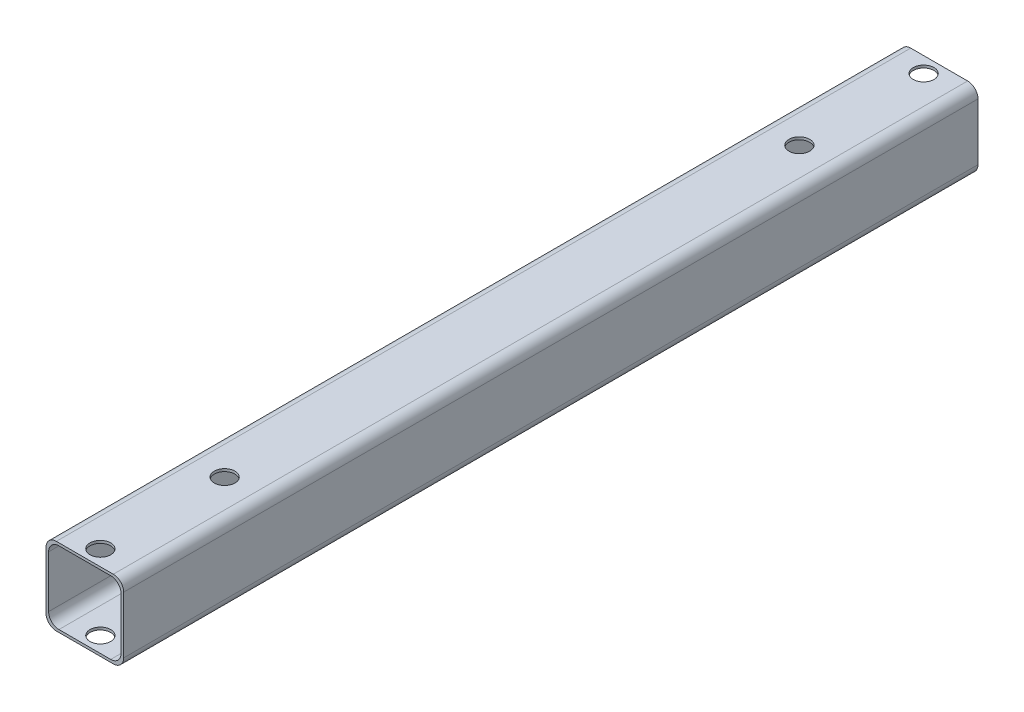
SolidWorks part; units mm, degrees
ref_plane "Front Plane" through (0, 0, 0) normal (0, 0, 1) x (1, 0, 0)
ref_plane "Top Plane" through (0, 0, 0) normal (0, 1, 0) x (1, 0, 0)
ref_plane "Right Plane" through (0, 0, 0) normal (1, 0, 0) x (0, 0, -1)
sketch "Sketch1" plane through (0, 0, 0) normal (0, 0, 1) x (1, 0, 0)
  line L1 (7.5, -7.5) -> (-7.5, -7.5)
  line L2 (7.5, -7.5) -> (7.5, 7.5)
  line L3 (7.5, 7.5) -> (-7.5, 7.5)
  line L4 (-7.5, -7.5) -> (-7.5, 7.5)
  line L5 (7.5, -7.5) -> (-7.5, 7.5) construction
  line L6 (7.5, 7.5) -> (-7.5, -7.5) construction
  line L7 (7, -7) -> (-7, -7)
  line L8 (7, -7) -> (7, 7)
  line L9 (7, 7) -> (-7, 7)
  line L10 (-7, -7) -> (-7, 7)
  line L11 (7, -7) -> (-7, 7) construction
  line L12 (7, 7) -> (-7, -7) construction
  point P0 (0, 0)
  point P6 (0, 0)
extrude "Boss-Extrude1" add sketch "Sketch1" along normal blind 165
fillet "Fillet1" radius 2 8 edges at (7, -7, 82.5) (7, 7, 82.5) (-7, -7, 82.5) (-7, 7, 82.5) (-7.5, -7.5, 82.5) (7.5, -7.5, 82.5) (7.5, 7.5, 82.5) (-7.5, 7.5, 82.5)
sketch "Sketch2" plane through (0, -7.5, 0) normal (0, -1, 0) x (1, 0, 0)
  line L0 (0, 0) -> (0, 3)
  circle A0 centre (0, 162) radius 2
  circle A1 centre (0, 138) radius 2
  circle A2 centre (0, 27) radius 2
  circle A3 centre (0, 3) radius 2
extrude "Cut-Extrude2" cut sketch "Sketch2" against normal blind 28
